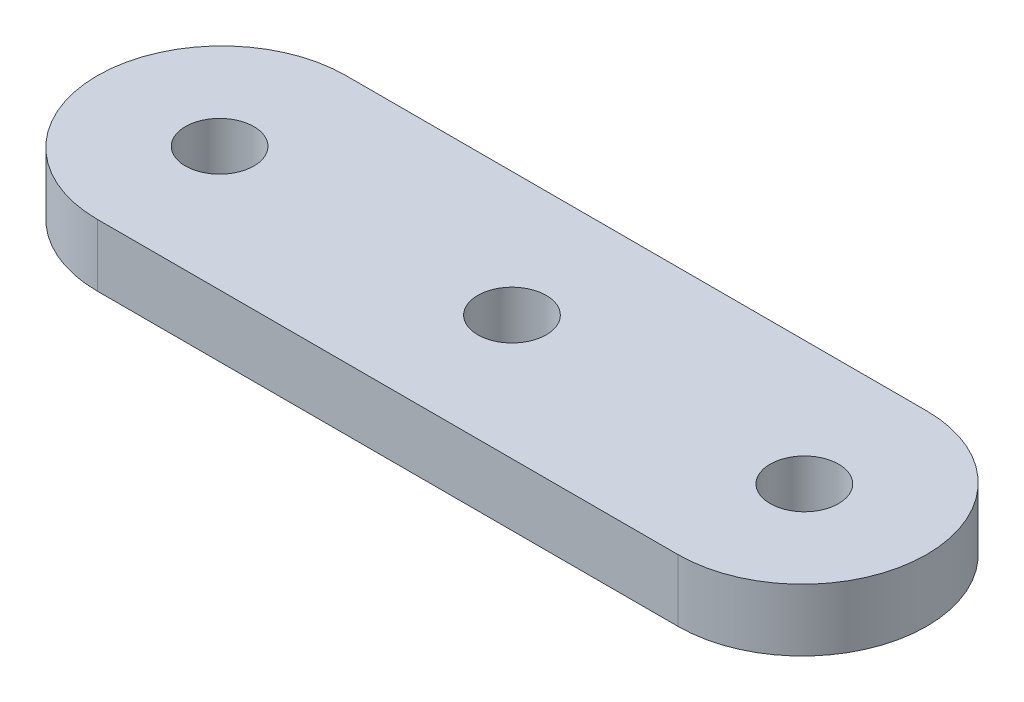
SolidWorks part; units mm, degrees
material "3003 Alloy"
ref_plane "Front Plane" through (0, 0, 0) normal (0, 0, 1) x (1, 0, 0)
ref_plane "Top Plane" through (0, 0, 0) normal (0, 1, 0) x (1, 0, 0)
ref_plane "Right Plane" through (0, 0, 0) normal (1, 0, 0) x (0, 0, -1)
sketch "Sketch1" plane through (0, 0, 0) normal (0, 1, 0) x (1, 0, 0)
  line L0 (14, 0) -> (-14, 0) construction
  line L1 (14, -6) -> (-14, -6)
  line L2 (14, 6) -> (-14, 6)
  arc A0 (14, -6) -> (14, 6) centre (14, 0) ccw
  arc A1 (-14, 6) -> (-14, -6) centre (-14, 0) ccw
  point P2 (0, 0)
  dimension "D1" = 6
  dimension "D2" = 28
extrude "Boss-Extrude1" add sketch "Sketch1" against normal blind 3
hole_wizard "M4x0.7 Tapped Hole1" positions "Sketch6" profile "Sketch7" tap size "M4x0.7" standard "ANSI Metric" end condition through all
sketch "Sketch6" plane through (0, 0, 0) normal (0, 1, 0) x (1, 0, 0)
  line L0 (-14.1, 0) -> (14.1, 0) construction
  point P0 (0, 0)
  point P3 (-14.1, 0)
  point P4 (14.1, 0)
  dimension "D1" = 14.1
  dimension "D2" = 14.1
cosmetic thread "Hole Thread1" parameters "D2"=5.4
cosmetic thread "Hole Thread2" parameters "D2"=5.4
cosmetic thread "Hole Thread3" parameters "D2"=5.4
sketch "Sketch7" plane through (0, 0, 0) normal (1, 0, 0) x (0, 0, 1)
  line L0 (0, 0) -> (0, 3)
  line L1 (0, 3) -> (1.65, 3)
  line L2 (1.65, 3) -> (1.65, 0)
  line L5 (1.65, 0) -> (0, 0)
  line L11 (0, -6.35) -> (0, 107.95) construction
  dimension "Thru Tap Drill Dia." = 3.3
  dimension "Thru Tap Drill Depth" = 3
